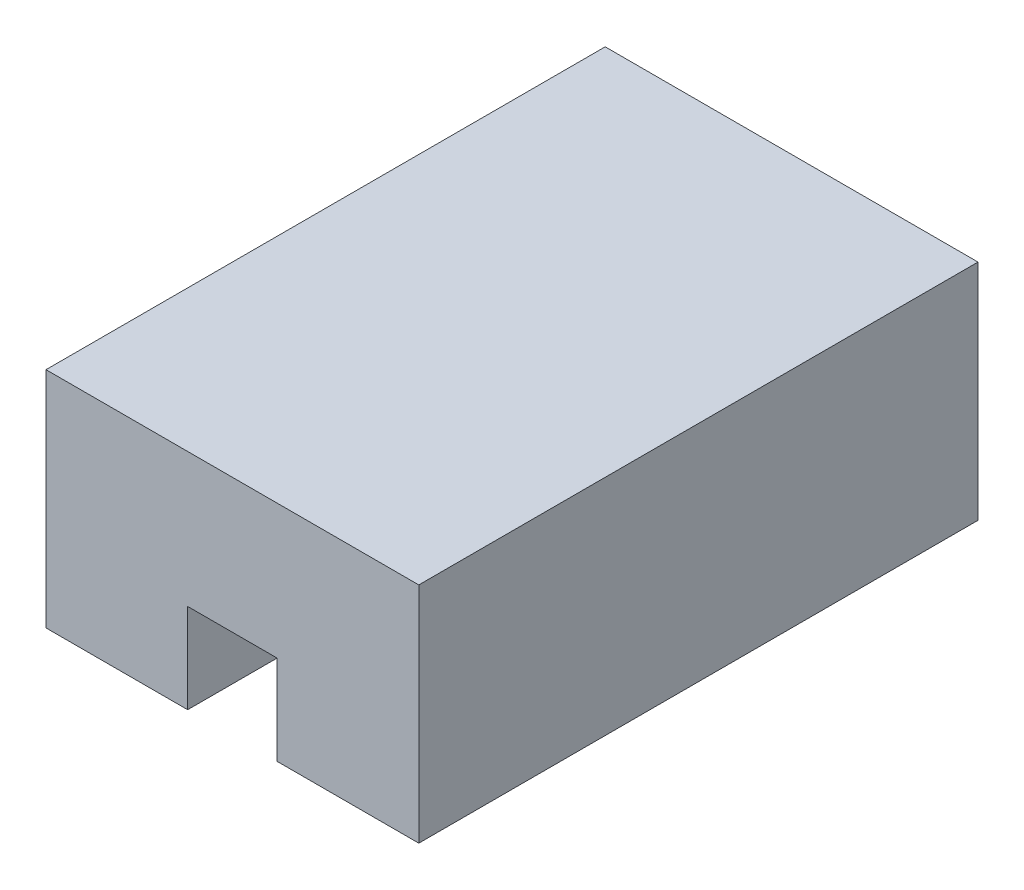
SolidWorks part; units mm, degrees
ref_plane "Alzado" through (0, 0, 0) normal (0, 0, 1) x (1, 0, 0)
ref_plane "Planta" through (0, 0, 0) normal (0, 1, 0) x (1, 0, 0)
ref_plane "Vista lateral" through (0, 0, 0) normal (1, 0, 0) x (0, 0, -1)
sketch "Croquis1" plane through (0, 0, 0) normal (0, 0, 1) x (1, 0, 0)
  line L0 (0, 0) -> (50, 0)
  line L1 (50, 0) -> (50, -30)
  line L2 (50, -30) -> (31, -30)
  line L3 (31, -30) -> (31, -18)
  line L4 (31, -18) -> (19, -18)
  line L5 (19, -18) -> (19, -30)
  line L6 (19, -30) -> (0, -30)
  line L7 (0, -30) -> (0, 0)
  dimension "D1" = 30
  dimension "D2" = 50
  dimension "D3" = 19
  dimension "D4" = 12
  dimension "D5" = 12
extrude "Saliente-Extruir1" add sketch "Croquis1" along normal blind 75
